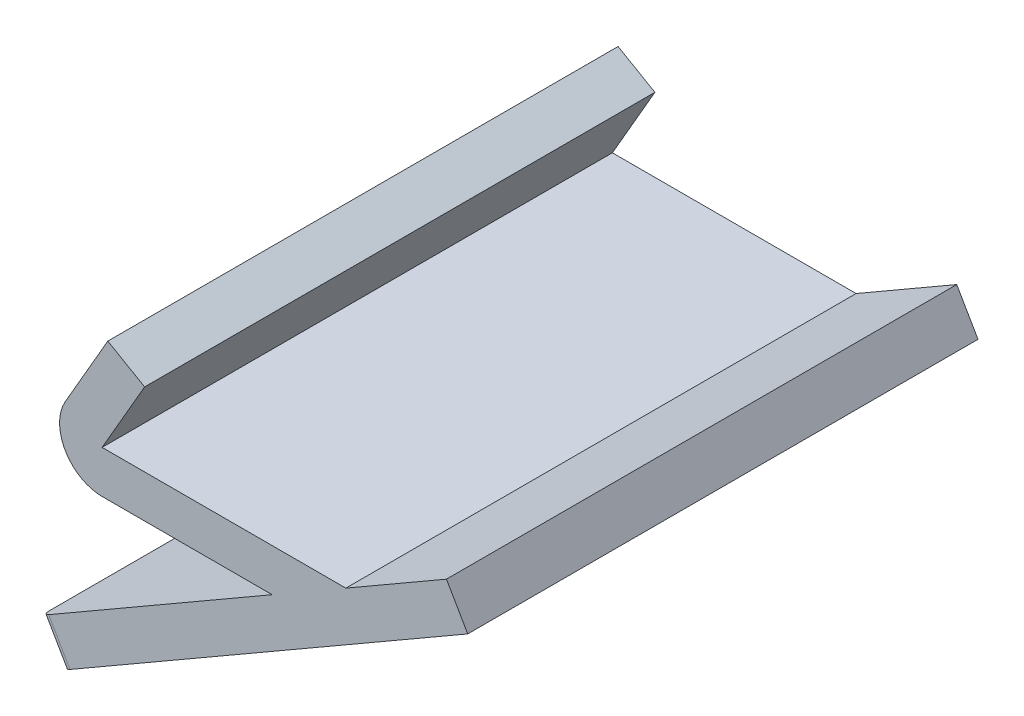
SolidWorks part; units mm, degrees
ref_plane "前视基准面" through (0, 0, 0) normal (0, 0, 1) x (1, 0, 0)
ref_plane "上视基准面" through (0, 0, 0) normal (0, 1, 0) x (1, 0, 0)
ref_plane "右视基准面" through (0, 0, 0) normal (1, 0, 0) x (0, 0, -1)
sketch "草图1" plane through (0, 0, 0) normal (0, 0, 1) x (1, 0, 0)
  line L1 (-19.2453, 11.2971) -> (10.7547, 11.2971)
  line L2 (-19.2453, 11.2971) -> (-19.2453, 6.2971)
  line L3 (-19.2453, 6.2971) -> (10.7547, 6.2971)
  line L4 (10.7547, 11.2971) -> (10.7547, 6.2971)
  dimension "D1" = 5
  dimension "D2" = 30
extrude "凸台-拉伸1" add sketch "草图1" along normal blind 60
sketch "草图2" plane through (0, 0, 60) normal (0, 0, 1) x (1, 0, 0)
  line L0 (-19.2453, 11.2971) -> (-14.2453, 19.9574)
  line L1 (-19.2453, 11.2971) -> (-23.5754, 13.7971)
  line L2 (-14.2453, 19.9574) -> (-18.5754, 22.4574)
  line L3 (-23.5754, 13.7971) -> (-18.5754, 22.4574)
  line L4 (10.7547, 11.2971) -> (-19.2453, 11.2971) construction
  point P7 (-16.7453, 15.6273)
  dimension "D1" = 60
  dimension "D2" = 5
  dimension "D3" = 10
extrude "凸台-拉伸2" add sketch "草图2" against normal blind 60 separate body
sketch "草图3" plane through (0, 0, 60) normal (0, 0, 1) x (1, 0, 0)
  line L4 (-23.5754, 13.7971) -> (-19.2453, 11.2971)
  line L5 (-19.2453, 11.2971) -> (-19.2453, 6.2971)
  arc A1 (-19.2453, 6.2971) -> (-23.5754, 13.7971) centre (-19.2453, 11.2971) cw
extrude "凸台-拉伸3" add sketch "草图3" against normal blind 60
sketch "草图4" plane through (0, 0, 60) normal (0, 0, 1) x (1, 0, 0)
  line L1 (10.7547, 6.2971) -> (-23.8863, -13.7029)
  line L2 (8.2547, 10.6273) -> (-26.3863, -9.3727)
  line L3 (-23.8863, -13.7029) -> (-26.3863, -9.3727)
  line L4 (-19.2453, 6.2971) -> (10.7547, 6.2971) construction
  line L7 (23.7451, 13.7971) -> (21.2451, 18.1273)
  line L8 (21.2451, 18.1273) -> (8.2547, 10.6273)
  line L9 (10.7547, 6.2971) -> (23.7451, 13.7971)
  dimension "D1" = 5
  dimension "D2" = 30
  dimension "D3" = 40
  dimension "D4" = 15
extrude "凸台-拉伸4" add sketch "草图4" against normal blind 60
hole_wizard "打孔尺寸(%根据)内六角圆柱头螺钉的类型1" positions "3D草图1" profile "草图6" counterbore size "M3" standard "GB" end condition through all
sketch3d "3D草图1"
  line L0 (0.7547, 6.2971, 60) -> (-26.3863, -9.3727, 60) construction
  line L1 (-26.3863, -9.3727, 0) -> (-26.3863, -9.3727, 60) construction
  point P0 (-21.158, -6.3542, 26.5001)
  point P2 (-21.1901, -6.3727, 33.5)
  dimension "D1" = 7
  dimension "D2" = 26.5
  dimension "D3" = 6
sketch "草图6" plane through (-21.158, -6.3542, 26.5001) normal (0, 0, 1) x (-0.866, -0.5, 0)
  line L0 (0, 0) -> (0, 28.8157)
  line L1 (0, 28.8157) -> (1.7, 28.8157)
  line L3 (1.7, 28.8157) -> (1.7, 3.4)
  line L4 (1.7, 3.4) -> (3, 3.4)
  line L5 (3, 3.4) -> (3, 0)
  line L7 (3, 0) -> (0, 0)
  line L11 (0, -6.35) -> (0, 107.95) construction
  dimension "通孔孔直径" = 3.4
  dimension "通孔孔深度" = 28.8157
  dimension "柱形沉头孔直径" = 6
  dimension "柱形沉头孔深度" = 3.4
sketch "草图7" plane through (-2.5381, 4.396, 0) normal (-0.5, 0.866, 0) x (0.866, 0.5, 0)
  line L0 (-26.5376, 0) -> (-27.5376, 0)
  line L1 (3.8022, 0) -> (-27.5376, 0) construction
  line L2 (-27.5376, 0) -> (-27.5376, -1)
  line L3 (-27.5376, 0) -> (-27.5376, -60) construction
  arc A0 (-27.5376, -1) -> (-26.5376, 0) centre (-26.5376, -1) cw
  dimension "D1" = 1
  dimension "D2" = 1
extrude "切除-拉伸1" cut sketch "草图7" against normal blind 60
sketch "草图9" plane through (-2.5381, 4.396, 0) normal (-0.5, 0.866, 0) x (0.866, 0.5, 0)
  line L0 (-27.5376, -59) -> (-27.5376, -60)
  line L1 (-27.5376, -1) -> (-27.5376, -60) construction
  line L2 (-27.5376, -60) -> (-26.5376, -60)
  line L3 (3.8022, -60) -> (-27.5376, -60) construction
  arc A0 (-26.5376, -60) -> (-27.5376, -59) centre (-26.5376, -59) cw
  dimension "D1" = 1
  dimension "D2" = 1
extrude "切除-拉伸2" cut sketch "草图9" against normal blind 60
